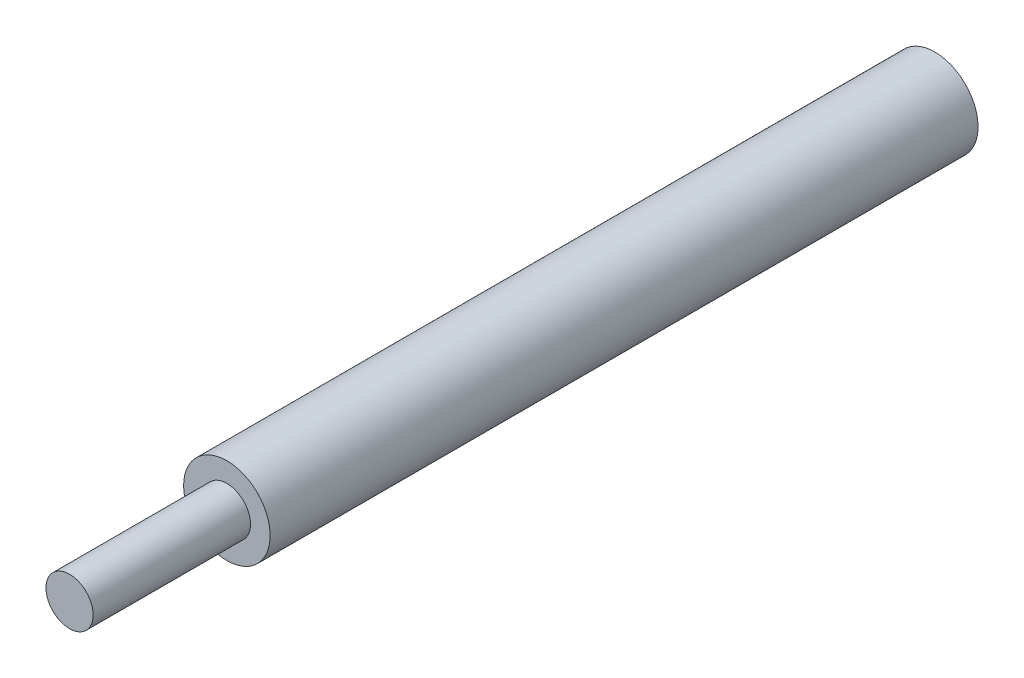
SolidWorks part; units mm, degrees
material "AISI 1020"
ref_plane "Plano superior" through (0, 0, 0) normal (0, 0, 1) x (1, 0, 0)
ref_plane "Plano frontal" through (0, 0, 0) normal (0, 1, 0) x (1, 0, 0)
ref_plane "Plano direito" through (0, 0, 0) normal (1, 0, 0) x (0, 0, -1)
sketch "Esboço2" plane through (0, 0, 0) normal (0, 0, 1) x (1, 0, 0)
  circle A0 centre (0, 0) radius 11
  dimension "D1" = 22
extrude "Ressalto-extrusão1" add sketch "Esboço2" along normal blind 180
sketch "Esboço11" plane through (0, 0, 180) normal (0, 0, 1) x (1, 0, 0)
  circle A0 centre (0, 0) radius 6
  dimension "D1" = 12
extrude "Ressalto-extrusão4" add sketch "Esboço11" along normal blind 41 contours A0
cosmetic thread "Representação de rosca1" parameters "D2"=10.072
sketch "Esboço15" plane through (0, 0, 221) normal (0, 0, 1) x (1, 0, 0)
  circle A0 centre (0, 0) radius 6
extrude "Corte-extrusão1" cut sketch "Esboço15" against normal blind 1
sketch "Esboço17" plane through (0, 0, 0) normal (0, 0, -1) x (-1, 0, 0)
  point P0 (0, 0)
hole_wizard "Furo roscado de M8x1.01" positions "Esboço18" profile "Esboço19" tap size "M8x1.0" standard "DIN"
sketch "Esboço18" plane through (0, 0, 0) normal (0, 0, -1) x (-1, 0, 0)
  point P0 (0, 0)
sketch "Esboço19" plane through (0, 0, 0) normal (1, 0, 0) x (0, 1, 0)
  line L0 (0, 0) -> (0, 37.103)
  line L1 (0, 37.103) -> (3.5, 35)
  line L2 (3.5, 35) -> (3.5, 0)
  line L5 (3.5, 0) -> (0, 0)
  line L10 (0, 37.103) -> (-3.5, 35) construction
  line L11 (0, -6.35) -> (0, 107.95) construction
  dimension "Tap Drill Dia." = 7
  dimension "Tap Drill Depth" = 35
  dimension "Drill Angle" = 118
cosmetic thread "Rosca de furo1" parameters "D1"=30, "D2"=8
